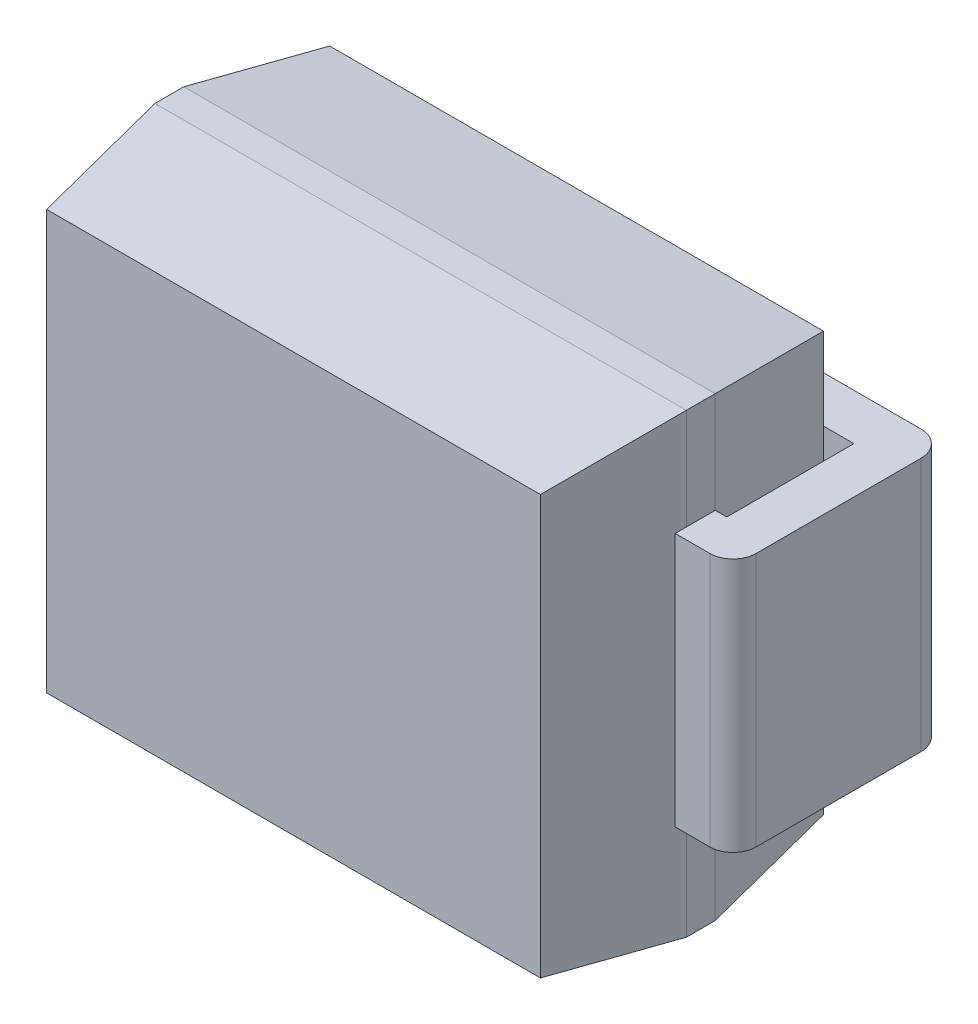
SolidWorks part; units mm, degrees
other "Детальный элемент1"
ref_plane "Спереди" through (0, 0, 0) normal (0, 0, 1) x (1, 0, 0)
ref_plane "Сверху" through (0, 0, 0) normal (0, 1, 0) x (1, 0, 0)
ref_plane "Справа" through (0, 0, 0) normal (1, 0, 0) x (0, 0, -1)
ref_plane "Плоскость1" through (0, 0, 0.4) normal (0, 0, 1) x (1, 0, 0)
sketch "Эскиз1" plane through (0, 0, 0.4) normal (0, 0, 1) x (1, 0, 0)
  line L1 (-2.3, 1.975) -> (2.3, 1.975)
  line L2 (-2.3, 1.975) -> (-2.3, -1.975)
  line L3 (-2.3, -1.975) -> (2.3, -1.975)
  line L4 (2.3, 1.975) -> (2.3, -1.975)
  line L5 (-2.3, 1.975) -> (2.3, -1.975) construction
  line L6 (-2.3, -1.975) -> (2.3, 1.975) construction
  point P0 (0, 0)
  dimension "D1" = 4.6
  dimension "D2" = 3.95
extrude "Бобышка-Вытянуть1" add sketch "Эскиз1" along normal blind 2.45
chamfer "Фаска1" distance 1.1 distance2 0.163 4 edges at (0, 1.975, 2.85) (2.3, 0, 2.85) (0, -1.975, 2.85) (-2.3, 0, 2.85)
chamfer "Фаска2" distance 0.163 distance2 1.1 4 edges at (2.3, 0, 0.4) (0, 1.975, 0.4) (0, -1.975, 0.4) (-2.3, 0, 0.4)
sketch "Эскиз2" plane through (0, 0, 0) normal (0, 1, 0) x (1, 0, 0)
  line L0 (-2.4, -0.4) -> (-2.4, -1.5)
  line L1 (-1.3, 0) -> (-2.58, 0)
  line L2 (-1.3, 0) -> (-1.3, -0.4)
  line L3 (-1.3, -0.4) -> (-2.4, -0.4)
  line L5 (-2.8, -1.6464) -> (-2.8, -0.22)
  line L6 (-2.6, -1.8464) -> (-2.3, -1.8464)
  line L7 (-2.3, -1.8464) -> (-2.3, -1.5)
  line L8 (-2.3, -1.5) -> (-2.4, -1.5)
  arc A2 (-2.6, -1.8464) -> (-2.8, -1.6464) centre (-2.6, -1.6464) cw
  arc A3 (-2.58, 0) -> (-2.8, -0.22) centre (-2.58, -0.22) ccw
  point P4 (0, 0)
  dimension "D3" = 0.22
  dimension "D6" = 0.2
  dimension "D1" = 0.4
  dimension "D2" = 0.4
  dimension "D4" = 1.5
  dimension "D5" = 0.5
extrude "Бобышка-Вытянуть2" add sketch "Эскиз2" along normal blind 1.1 and the other way blind 1.1 separate body
mirror "Зеркальное отражение1" about plane through (0, 0, 0) normal (1, 0, 0) of bodies 108
